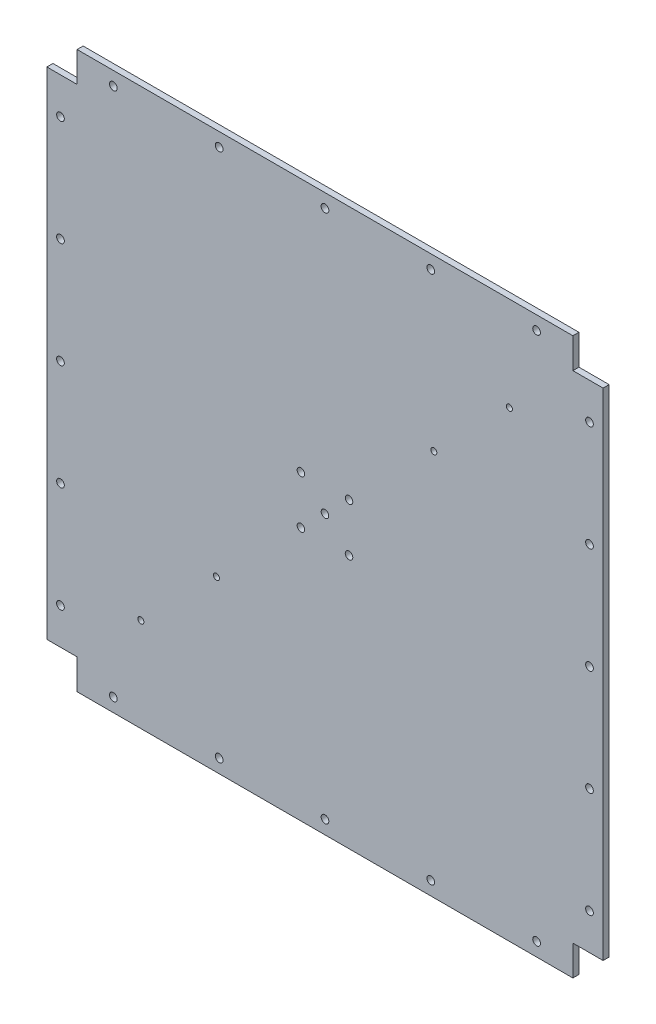
SolidWorks part; units mm, degrees
ref_plane "前视基准面" through (0, 0, 0) normal (0, 0, 1) x (1, 0, 0)
ref_plane "上视基准面" through (0, 0, 0) normal (0, 1, 0) x (1, 0, 0)
ref_plane "右视基准面" through (0, 0, 0) normal (1, 0, 0) x (0, 0, -1)
sketch "草图1" plane through (0, 0, 0) normal (0, 0, 1) x (1, 0, 0)
  line L1 (184, -184) -> (-184, -184)
  line L2 (184, -184) -> (184, 184)
  line L3 (184, 184) -> (-184, 184)
  line L4 (-184, -184) -> (-184, 184)
  line L5 (184, -184) -> (-184, 184) construction
  line L6 (184, 184) -> (-184, -184) construction
  point P0 (0, 0)
  dimension "D1" = 368
  dimension "D2" = 368
extrude "凸台-拉伸1" add sketch "草图1" along normal blind 4
sketch "草图3" plane through (0, 0, 4) normal (0, 0, 1) x (1, 0, 0)
  line L0 (0, -184) -> (0, -175) construction
  line L1 (-184, -184) -> (184, -184) construction
  circle A0 centre (0, -175) radius 2.55
  circle A1 centre (70, -175) radius 2.55
  circle A2 centre (140, -175) radius 2.55
  circle A3 centre (-70, -175) radius 2.55
  circle A4 centre (-140, -175) radius 2.55
  circle A30 centre (-175, 140) radius 2.55
  circle A31 centre (-175, 70) radius 2.55
  circle A32 centre (-175, -70) radius 2.55
  circle A33 centre (-175, -140) radius 2.55
  circle A34 centre (-175, 0) radius 2.55
  circle A35 centre (140, 175) radius 2.55
  circle A36 centre (70, 175) radius 2.55
  circle A37 centre (-70, 175) radius 2.55
  circle A38 centre (-140, 175) radius 2.55
  circle A39 centre (0, 175) radius 2.55
  circle A40 centre (175, -140) radius 2.55
  circle A41 centre (175, -70) radius 2.55
  circle A42 centre (175, 70) radius 2.55
  circle A43 centre (175, 140) radius 2.55
  circle A44 centre (175, 0) radius 2.55
  point P47 (10, -10)
  point P78 (0, 0)
  dimension "D1" = 5.1
  dimension "D2" = 9
  dimension "D3" = 3
  dimension "D4" = 3
  dimension "D6" = 4
extrude "切除-拉伸2" cut sketch "草图3" against normal through all
sketch "草图4" plane through (0, 0, 4) normal (0, 0, 1) x (1, 0, 0)
  line L0 (-164, 184) -> (-164, 164)
  line L1 (-184, -184) -> (-164, -184)
  line L2 (-184, -184) -> (-184, -164)
  line L3 (-184, -164) -> (-164, -164)
  line L4 (-164, -184) -> (-164, -164)
  line L5 (-184, 164) -> (-164, 164)
  line L6 (-184, 184) -> (-164, 184)
  line L7 (-184, 184) -> (-184, 164)
  line L8 (184, 164) -> (164, 164)
  line L9 (164, 184) -> (164, 164)
  line L10 (184, 184) -> (184, 164)
  line L11 (184, 184) -> (164, 184)
  line L12 (164, -184) -> (164, -164)
  line L13 (184, -164) -> (164, -164)
  line L14 (184, -184) -> (164, -184)
  line L15 (184, -184) -> (184, -164)
  point P20 (0, 0)
  dimension "D1" = 20
  dimension "D2" = 20
  dimension "D3" = 4
extrude "切除-拉伸3" cut sketch "草图4" against normal through all contours L0 L5 L7 L6 | L8 L9 L11 L10 | L12 L13 L15 L14 | L2 L1 L4 L3
sketch "草图5" plane through (0, 0, 4) normal (0, 0, 1) x (1, 0, 0)
  line L0 (-184, 0) -> (184, 0) construction
  line L1 (-184, 164) -> (-184, -164) construction
  line L3 (0, 184) -> (0, -184) construction
  line L4 (164, 184) -> (-164, 184) construction
  line L5 (-164, -184) -> (164, -184) construction
  line L6 (-10, 0) -> (-22.5, 0) construction
  line L11 (10, -10) -> (-10, 10) construction
  line L12 (10, 10) -> (-10, -10) construction
  line L13 (0, -10) -> (0, -22.5) construction
  line L14 (10, 0) -> (22.5, 0) construction
  line L15 (0, 10) -> (0, 22.5) construction
  line L16 (-173.9781, 173.9781) -> (0, 0) construction
  line L17 (-184, 0) -> (0, 184) construction
  line L18 (0, 0) -> (-15.9099, 15.9099) construction
  line L19 (-14.489, 14.489) -> (-159.489, 14.489) construction
  line L20 (-14.489, 14.489) -> (-14.489, 159.489) construction
  line L21 (-14.489, 159.489) -> (-159.489, 159.489) construction
  line L22 (-159.489, 14.489) -> (-159.489, 159.489) construction
  line L23 (-14.489, 14.489) -> (-159.489, 159.489) construction
  line L24 (-14.489, 159.489) -> (-159.489, 14.489) construction
  line L25 (0, 0) -> (15.9099, 15.9099) construction
  circle A4 centre (0, 0) radius 2.5
  circle A5 centre (-15.9099, 15.9099) radius 2.5
  circle A7 centre (15.9099, 15.9099) radius 2.5
  circle A8 centre (15.9099, -15.9099) radius 2.5
  circle A9 centre (-15.9099, -15.9099) radius 2.5
  point P4 (-86.989, 86.989)
  point P12 (0, 0)
  dimension "D11" = 5
  dimension "D16" = 5
  dimension "D17" = 5
  dimension "D1" = 20
  dimension "D2" = 20
  dimension "D3" = 12.5
  dimension "D4" = 12.5
  dimension "D5" = 12.5
  dimension "D6" = 12.5
  dimension "D12" = 145
  dimension "D13" = 145
  dimension "D14" = 22.5
  dimension "D15" = 22.5
extrude "切除-拉伸6" cut sketch "草图5" against normal blind 10
sketch "草图6" plane through (0, 0, 0) normal (0, 0, -1) x (-1, 0, 0)
  line L0 (-164, -164) -> (164, 164)
  circle A0 centre (121.8, -122) radius 2
  circle A1 centre (71.8, -72) radius 2
  circle A2 centre (-122, 121.8) radius 2
  circle A3 centre (-72, 71.8) radius 2
  point P22 (0, 0)
  point P23 (0, 0)
extrude "切除-拉伸7" cut sketch "草图6" against normal blind 10 contours A2 | A3 | A1 | A0
